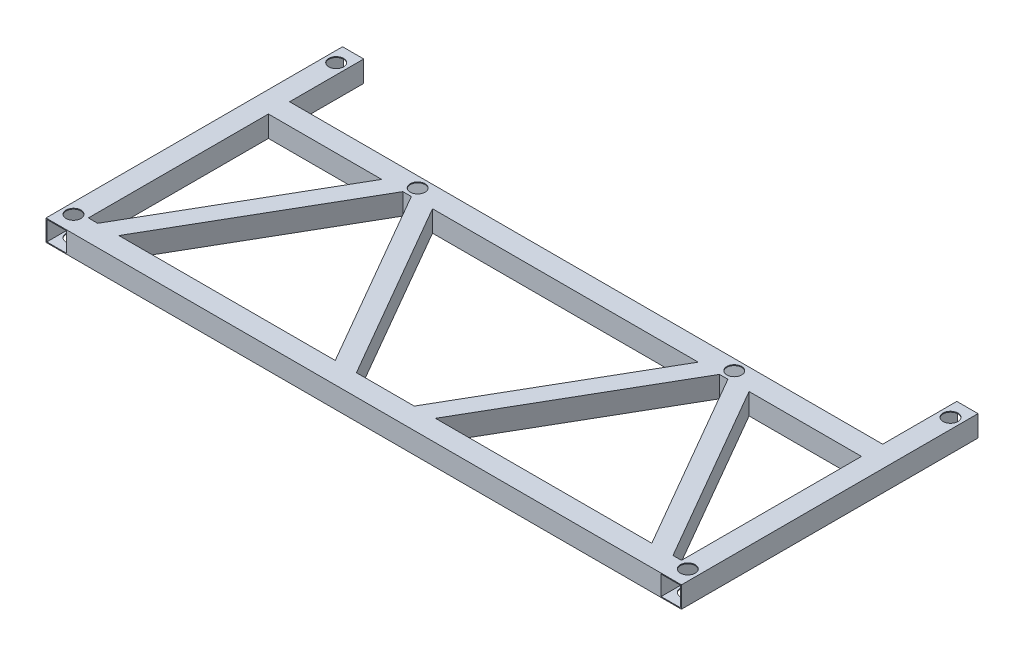
SolidWorks part; units mm, degrees
ref_plane "Front Plane" through (0, 0, 0) normal (0, 0, 1) x (1, 0, 0)
ref_plane "Top Plane" through (0, 0, 0) normal (0, 1, 0) x (1, 0, 0)
ref_plane "Right Plane" through (0, 0, 0) normal (1, 0, 0) x (0, 0, -1)
sketch "Sketch1" plane through (0, 0, 0) normal (0, 0, 1) x (1, 0, 0)
  line L1 (-25, -25) -> (25, -25)
  line L2 (-25, -25) -> (-25, 25)
  line L3 (-25, 25) -> (25, 25)
  line L4 (25, -25) -> (25, 25)
  line L5 (-25, -25) -> (25, 25) construction
  line L6 (-25, 25) -> (25, -25) construction
  point P0 (0, 0)
  dimension "D1" = 50
  dimension "D2" = 50
extrude "Extrude-Thin1" add sketch "Sketch1" along normal blind 700 thin thin type one direction reverse wall 2
sketch "Sketch2" plane through (25, 0, 0) normal (1, 0, 0) x (0, 0, -1)
  line L0 (-700, -25) -> (-700, 25)
  line L1 (-700, -25) -> (-650, -25)
  line L2 (-700, 25) -> (-650, 25)
  line L3 (-650, -25) -> (-650, 25)
  line L4 (-698, -23) -> (-698, 23)
  line L5 (-698, 23) -> (-652, 23)
  line L6 (-652, -23) -> (-652, 23)
  line L7 (-698, -23) -> (-652, -23)
  dimension "D1" = 50
  dimension "D2" = 2
extrude "Boss-Extrude1" add sketch "Sketch2" along normal blind 1400
sketch "Sketch4" plane through (0, 0, 700) normal (0, 0, 1) x (1, 0, 0)
  line L0 (1425, 25) -> (1425, -25)
  line L1 (1425, 25) -> (1475, 25)
  line L2 (1425, -25) -> (1475, -25)
  line L3 (1475, 25) -> (1475, -25)
  dimension "D1" = 50
extrude "Extrude-Thin7" add sketch "Sketch4" against normal blind 700 thin thin type one direction reverse wall 2
sketch "Sketch6" plane through (25, 0, 0) normal (1, 0, 0) x (0, 0, -1)
  line L0 (-225, -25) -> (-225, 25)
  line L1 (-225, -25) -> (-175, -25)
  line L2 (-225, 25) -> (-175, 25)
  line L3 (-175, -25) -> (-175, 25)
  line L4 (-650, -25) -> (0, -25) construction
  line L5 (-650, 25) -> (0, 25) construction
  line L6 (0, -25) -> (0, 25) construction
  line L7 (-223, -23) -> (-177, -23)
  line L8 (-177, -23) -> (-177, 23)
  line L9 (-223, 23) -> (-177, 23)
  line L10 (-223, -23) -> (-223, 23)
  dimension "D1" = 50
  dimension "D2" = 50
  dimension "D3" = 175
  dimension "D4" = 2
extrude "Boss-Extrude2" add sketch "Sketch6" along normal up to surface (1400 mm away) up to face at (1425, 0, 325)
sketch "Sketch7" plane through (0, 0, 650) normal (0, 0, -1) x (-1, 0, 0)
  line L0 (-1405, -25) -> (-1405, 25)
  line L1 (-1405, -25) -> (-1355, -25)
  line L2 (-1405, 25) -> (-1355, 25)
  line L3 (-1355, -25) -> (-1355, 25)
  line L4 (-1425, -25) -> (-25, -25) construction
  line L5 (-1425, 25) -> (-25, 25) construction
  line L6 (-1425, 25) -> (-1425, -25) construction
  line L7 (-1380, -25) -> (-1380, 25) construction
  dimension "D1" = 50
  dimension "D2" = 20
ref_plane "Plane1" through (753.5417, 0, -435.0575) normal (-0.866, 0, 0.5) x (0, 1, 0)
sketch "Sketch10" plane through (753.5417, 0, -435.0575) normal (-0.866, 0, 0.5) x (0, 1, 0)
  line L0 (-5.3231, -1436.9988) -> (-5.3231, -750.4337)
sweep "Sweep1" add profiles "Sketch7" path "Sketch10"
sketch "Sketch11" plane through (0, 0, 225) normal (0, 0, 1) x (1, 0, 0)
  line L0 (1109.6261, 25) -> (25, 25) construction
  line L1 (1089.6261, 25) -> (1039.6261, 25)
  line L2 (1089.6261, 25) -> (1089.6261, -25)
  line L3 (1089.6261, -25) -> (1039.6261, -25)
  line L4 (1039.6261, 25) -> (1039.6261, -25)
  line L5 (1109.6261, -25) -> (25, -25) construction
  line L6 (1109.6261, -25) -> (1109.6261, 25) construction
  line L7 (1064.6261, 25) -> (1064.6261, -25) construction
  dimension "D1" = 50
  dimension "D2" = 50
  dimension "D3" = 20
ref_plane "Plane2" through (895.8975, 0, 517.2466) normal (-0.866, 0, -0.5) x (0, -1, 0)
sketch "Sketch12" plane through (895.8975, 0, 517.2466) normal (-0.866, 0, -0.5) x (0, -1, 0)
  line L0 (0, -341.1032) -> (0, 158.99)
sweep "Sweep2" add profiles "Sketch11" path "Sketch12"
pattern_linear "LPattern1" count 2 spacing 747.25 along (-1, 0, 0) of "Sweep1", "Sweep2"
sketch "Sketch17" plane through (0, -25, 0) normal (0, -1, 0) x (1, 0, 0)
  line L0 (-25, 700) -> (1475, 700) construction
  line L1 (-25, 0) -> (25, 0) construction
  line L2 (1425, 0) -> (1475, 0) construction
  line L3 (1475, 0) -> (1475, 700) construction
  line L4 (-25, 700) -> (-25, 0) construction
  line L5 (25, 650) -> (25, 225) construction
  circle A0 centre (0, 660) radius 17.5
  circle A1 centre (0, 40) radius 17.5
  circle A2 centre (1450, 40) radius 17.5
  circle A4 centre (1450, 660) radius 17.5
  point P0 (0, 660)
  point P1 (0, 40)
  point P2 (1450, 40)
  point P3 (1450, 660)
  dimension "D11" = 35
  dimension "D12" = 35
  dimension "D13" = 35
  dimension "D14" = 35
  dimension "D1" = 40
  dimension "D2" = 40
  dimension "D3" = 40
  dimension "D4" = 40
  dimension "D5" = 25
  dimension "D6" = 25
  dimension "D7" = 25
  dimension "D8" = 25
  dimension "D9" = 25
  dimension "D10" = 25
extrude "Cut-Extrude1" cut sketch "Sketch17" against normal through all
sketch "Sketch18" plane through (0, -25, 0) normal (0, -1, 0) x (1, 0, 0)
  line L0 (362.3761, 225) -> (342.3761, 225) construction
  line L1 (1425, 175) -> (25, 175) construction
  line L2 (1109.6261, 225) -> (1089.6261, 225) construction
  circle A0 centre (352.3761, 200) radius 17.5
  circle A1 centre (1099.6261, 200) radius 17.5
  point P0 (352.3761, 200)
  point P1 (1099.6261, 200)
  dimension "D4" = 35
  dimension "D5" = 35
  dimension "D1" = 25
  dimension "D2" = 25
  dimension "D3" = 25
extrude "Cut-Extrude2" cut sketch "Sketch18" against normal through all
